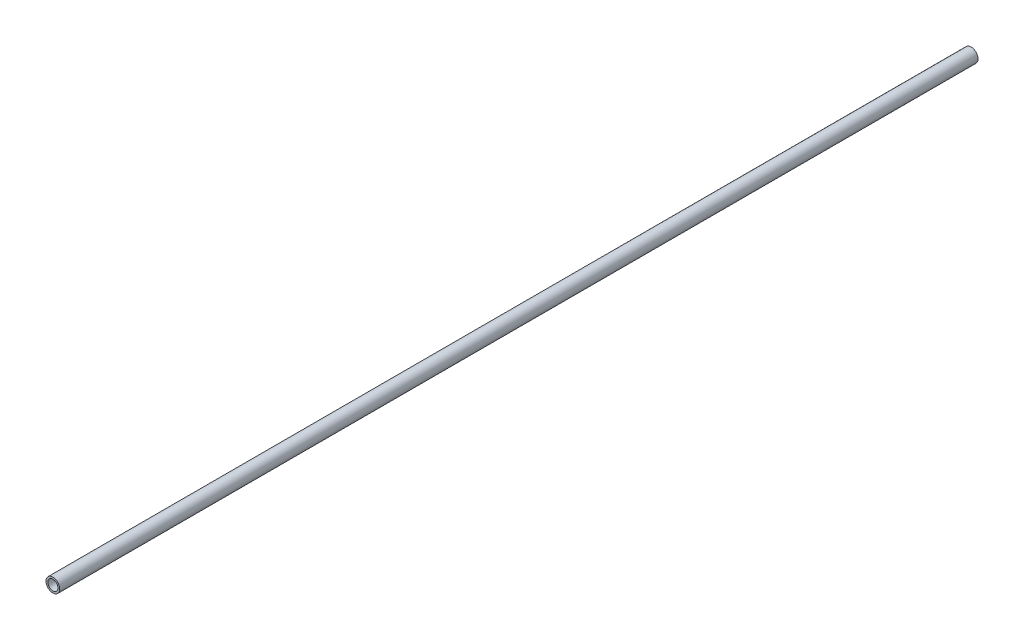
SolidWorks part; units mm, degrees
ref_plane "Front Plane" through (0, 0, 0) normal (0, 0, 1) x (1, 0, 0)
ref_plane "Top Plane" through (0, 0, 0) normal (0, 1, 0) x (1, 0, 0)
ref_plane "Right Plane" through (0, 0, 0) normal (1, 0, 0) x (0, 0, -1)
sketch "Sketch1" plane through (0, 0, 0) normal (0, 0, 1) x (1, 0, 0)
  circle A0 centre (-32.8993, 249.8477) radius 3.75
  circle A1 centre (-32.8993, 249.8477) radius 2.75
  dimension "D1" = 1
extrude "Boss-Extrude1" add sketch "Sketch1" along normal blind 500
